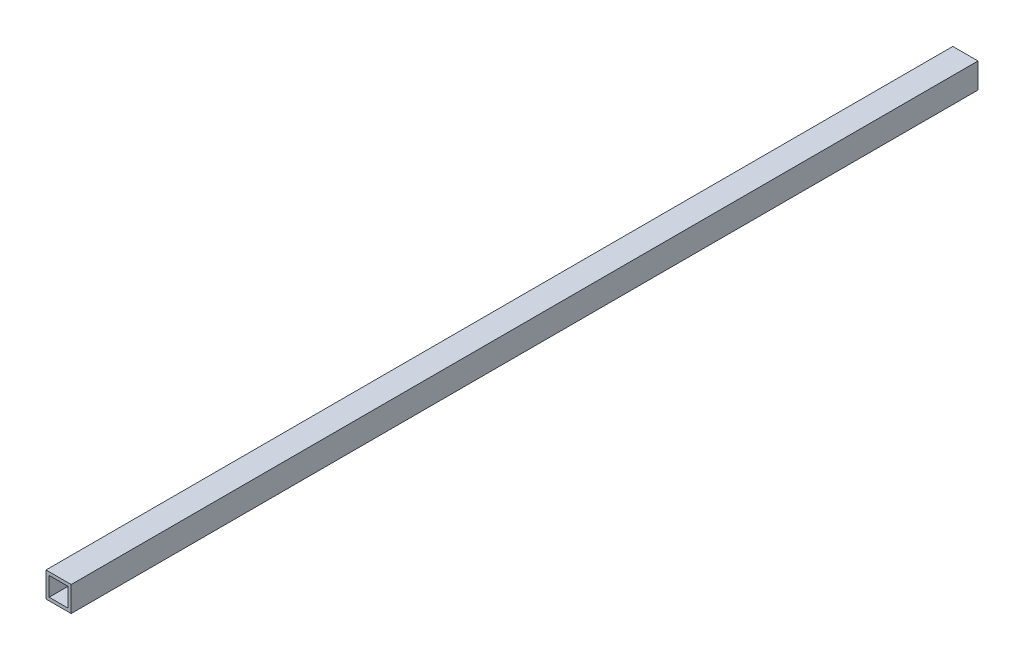
SolidWorks part; units mm, degrees
ref_plane "Front Plane" through (0, 0, 0) normal (0, 0, 1) x (1, 0, 0)
ref_plane "Top Plane" through (0, 0, 0) normal (0, 1, 0) x (1, 0, 0)
ref_plane "Right Plane" through (0, 0, 0) normal (1, 0, 0) x (0, 0, -1)
sketch "Sketch1" plane through (0, 0, 0) normal (0, 0, 1) x (1, 0, 0)
  line L0 (-9.525, 9.525) -> (9.525, 9.525)
  line L2 (-12.7, 12.7) -> (12.7, 12.7)
  line L3 (-12.7, 12.7) -> (-12.7, -12.7)
  line L4 (-12.7, -12.7) -> (12.7, -12.7)
  line L5 (12.7, 12.7) -> (12.7, -12.7)
  line L10 (9.525, 9.525) -> (9.525, -9.525)
  line L11 (-9.525, -9.525) -> (9.525, -9.525)
  line L12 (-9.525, 9.525) -> (-9.525, -9.525)
  point P12 (0, 12.7)
  point P14 (12.7, 0)
  dimension "Wall Thickness" = 3.175
  dimension "Outside Width" = 25.4
  dimension "Outside Height" = 25.4
  dimension "Inside Height" = 19.05
  dimension "Inside Width" = 19.05
sketch "Sketch2" plane through (0, 0, 0) normal (1, 0, 0) x (0, 0, -1)
  line L0 (457.2, 0) -> (-457.2, 0)
  point P4 (0, 0)
  point P7 (-457.2, 0)
  point P10 (457.2, 0)
  dimension "Length" = 914.4
sketch "Sketch3" plane through (0, 0, 0) normal (0, 0, 1) x (1, 0, 0)
  line L21 (12.7, 12.7) -> (-12.7, 12.7)
  line L22 (12.7, -12.7) -> (12.7, 12.7)
  line L23 (-12.7, -12.7) -> (12.7, -12.7)
  line L24 (-12.7, 12.7) -> (-12.7, -12.7)
  line L25 (12.7, 12.7) -> (-12.7, 12.7)
  line L26 (12.7, -12.7) -> (12.7, 12.7)
  line L27 (-12.7, -12.7) -> (12.7, -12.7)
  line L28 (-12.7, 12.7) -> (-12.7, -12.7)
  line L29 (9.525, 9.525) -> (-9.525, 9.525)
  line L30 (9.525, -9.525) -> (9.525, 9.525)
  line L31 (-9.525, -9.525) -> (9.525, -9.525)
  line L32 (-9.525, 9.525) -> (-9.525, -9.525)
  line L33 (9.525, 9.525) -> (-9.525, 9.525)
  line L34 (9.525, -9.525) -> (9.525, 9.525)
  line L35 (-9.525, -9.525) -> (9.525, -9.525)
  line L36 (-9.525, 9.525) -> (-9.525, -9.525)
  dimension "D1" = 0
  dimension "D2" = 0
extrude "Boss-Extrude1" add sketch "Sketch3" along normal up to vertex (457.2 mm away) and the other way up to vertex (457.2 mm away) up to point (0, 0, 457.2) other way up to point (0, 0, -457.2)
sketch "Drawing Reference" plane through (0, 0, 0) normal (1, 0, 0) x (0, 0, -1)
  line L0 (-457.2, 0) -> (457.2, 0) construction
  line L1 (0, -12.7) -> (0, 12.7) construction
  line L2 (-457.2, -12.7) -> (457.2, -12.7) construction
  line L5 (-457.2, 12.7) -> (457.2, 12.7) construction
  point P7 (-438.912, 0)
  point P8 (438.912, 0)
  dimension "D1" = 18.288
equation "\"D1@Drawing Reference\"=\"Outside Width@Sketch1\" * 0.72"
